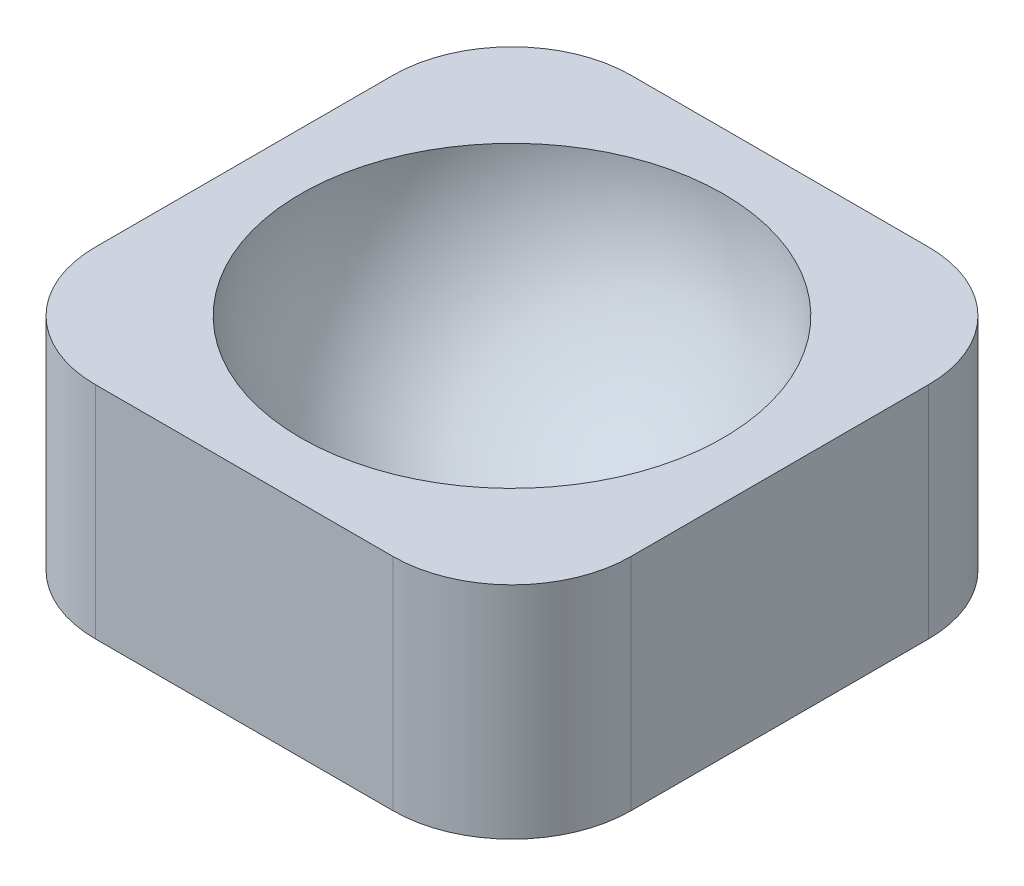
SolidWorks part; units mm, degrees
material "AISI 4340 Steel, normalized"
ref_plane "Front Plane" through (0, 0, 0) normal (0, 0, 1) x (1, 0, 0)
ref_plane "Top Plane" through (0, 0, 0) normal (0, 1, 0) x (1, 0, 0)
ref_plane "Right Plane" through (0, 0, 0) normal (1, 0, 0) x (0, 0, -1)
sketch "Sketch1" plane through (0, 0, 0) normal (0, 1, 0) x (1, 0, 0)
  line L1 (0, 0) -> (-114.3, 0)
  line L2 (0, 0) -> (0, 114.3)
  line L3 (0, 114.3) -> (-114.3, 114.3)
  line L4 (-114.3, 0) -> (-114.3, 114.3)
  circle A0 centre (-57.15, 57.15) radius 44.45
  point P7 (-101.6, 57.15)
  point P8 (-114.3, 57.15)
  point P9 (0, 57.15)
  point P10 (-57.15, 114.3)
  point P11 (-57.15, 0)
  point P13 (-57.15, 101.6)
  dimension "D1" = 88.9
  dimension "D2" = 12.7
  dimension "D3" = 12.7
extrude "Boss-Extrude1" add sketch "Sketch1" along normal blind 46.99 contours L4 L1 L2 L3 A0 | A0
sketch "Sketch2" plane through (0, 46.99, 0) normal (0, 1, 0) x (1, 0, 0)
  line L0 (-57.15, 114.3) -> (-57.15, 0) construction
  line L1 (0, 114.3) -> (-114.3, 114.3) construction
  line L2 (0, 0) -> (-114.3, 0) construction
  line L3 (-57.15, 102.235) -> (-57.15, 12.065)
  circle A0 centre (-57.15, 57.15) radius 45.085
  dimension "D1" = 90.17
revolve "Cut-Revolve1" cut sketch "Sketch2" angle 180 about L0
fillet "Fillet1" radius 25.4 4 edges at (0, 23.495, 0) (-114.3, 23.495, 0) (-114.3, 23.495, -114.3) (0, 23.495, -114.3)
sketch "Sketch3" plane through (0, 0, 0) normal (0, -1, 0) x (1, 0, 0)
  line L0 (-57.15, -114.3) -> (-57.15, 0) construction
  line L1 (-25.4, -114.3) -> (-88.9, -114.3) construction
  line L2 (-25.4, 0) -> (-88.9, 0) construction
  line L3 (0, -57.15) -> (-114.3, -57.15) construction
  line L4 (0, -25.4) -> (0, -88.9) construction
  line L5 (-114.3, -25.4) -> (-114.3, -88.9) construction
sketch "Sketch4" plane through (0, 0, 0) normal (0, -1, 0) x (1, 0, 0)
  line L0 (0, -57.15) -> (-114.3, -57.15) construction
  line L1 (0, -25.4) -> (0, -88.9) construction
  line L2 (-114.3, -25.4) -> (-114.3, -88.9) construction
  line L3 (-57.15, -114.3) -> (-57.15, 0) construction
  line L4 (-25.4, -114.3) -> (-88.9, -114.3) construction
  line L5 (-25.4, 0) -> (-88.9, 0) construction
  point P12 (-57.15, -57.15)
equation "\"D3@Sketch1\"=\"D2@Sketch1\""
